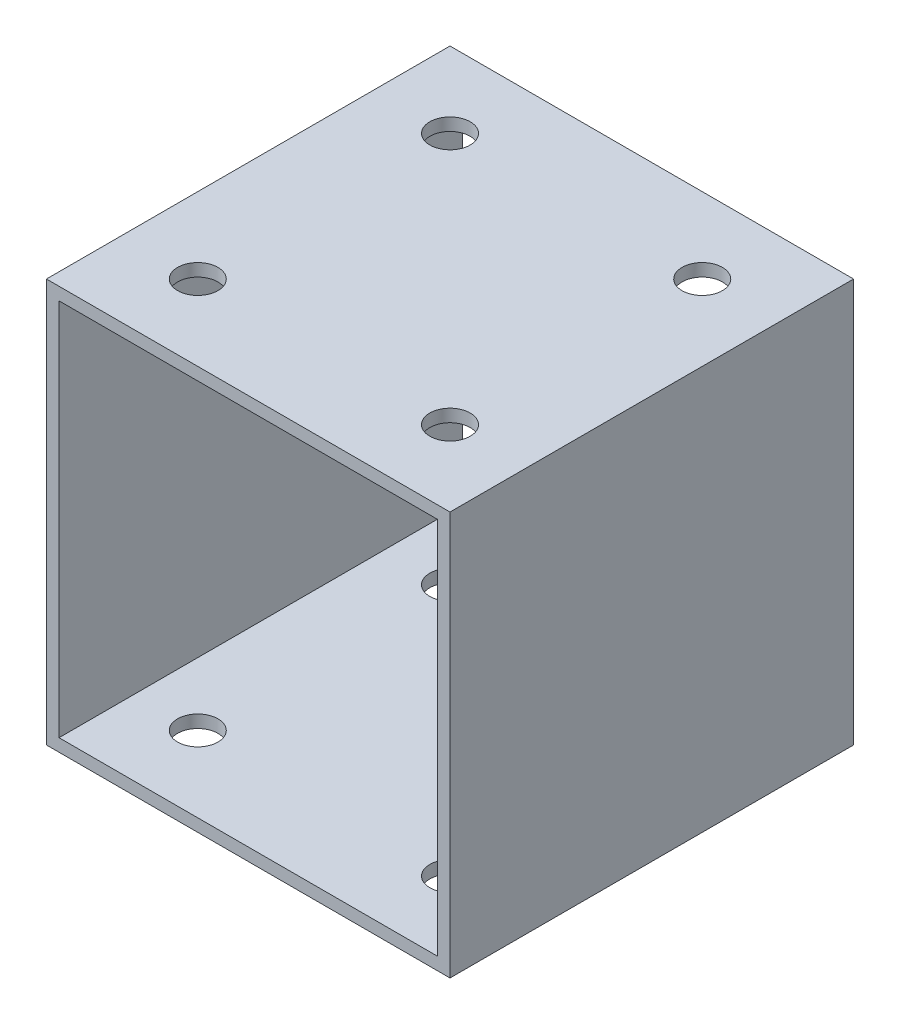
SolidWorks part; units mm, degrees
material "1060 Alloy"
ref_plane "Front Plane" through (0, 0, 0) normal (0, 0, 1) x (1, 0, 0)
ref_plane "Top Plane" through (0, 0, 0) normal (0, 1, 0) x (1, 0, 0)
ref_plane "Right Plane" through (0, 0, 0) normal (1, 0, 0) x (0, 0, -1)
sketch "Sketch2" plane through (0, 0, 0) normal (0, 0, 1) x (1, 0, 0)
  line L1 (0, 0) -> (50.8, 0)
  line L2 (0, 0) -> (0, 50.8)
  line L3 (0, 50.8) -> (50.8, 50.8)
  line L4 (50.8, 0) -> (50.8, 50.8)
  line L5 (1.5875, 1.5875) -> (49.2125, 1.5875)
  line L6 (1.5875, 1.5875) -> (1.5875, 49.2125)
  line L7 (1.5875, 49.2125) -> (49.2125, 49.2125)
  line L8 (49.2125, 1.5875) -> (49.2125, 49.2125)
  dimension "D1" = 50.8
  dimension "D2" = 50.8
  dimension "D3" = 1.5875
  dimension "D4" = 1.5875
  dimension "D5" = 1.5875
  dimension "D6" = 1.5875
extrude "Boss-Extrude1" add sketch "Sketch2" along normal blind 50.8
sketch "Sketch3" plane through (0, 50.8, 0) normal (0, 1, 0) x (1, 0, 0)
  line L0 (50.8, -50.8) -> (50.8, 0) construction
  line L1 (50.8, 0) -> (0, 0) construction
  line L2 (50.8, -50.8) -> (0, -50.8) construction
  line L3 (0, -50.8) -> (0, 0) construction
  circle A0 centre (41.275, -9.525) radius 2.54
  circle A1 centre (41.275, -41.275) radius 2.54
  circle A2 centre (9.525, -9.525) radius 2.54
  circle A3 centre (9.525, -41.275) radius 2.54
  dimension "D1" = 5.08
  dimension "D2" = 9.525
  dimension "D3" = 9.525
  dimension "D4" = 9.525
  dimension "D5" = 9.525
extrude "Cut-Extrude1" cut sketch "Sketch3" against normal through all
